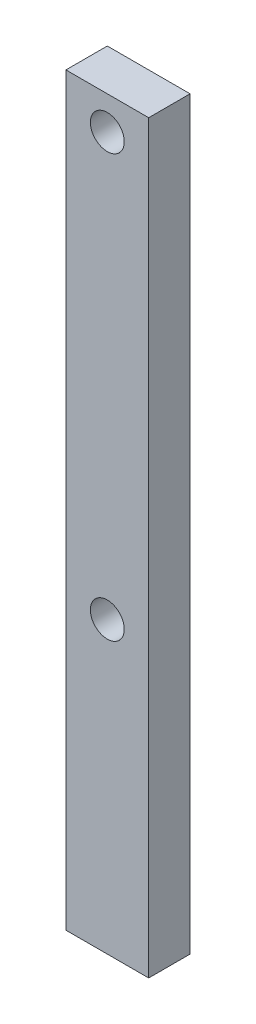
SolidWorks part; units mm, degrees
material "Pin"
ref_plane "Front" through (0, 0, 0) normal (0, 0, 1) x (1, 0, 0)
ref_plane "Top" through (0, 0, 0) normal (0, 1, 0) x (1, 0, 0)
ref_plane "Right" through (0, 0, 0) normal (1, 0, 0) x (0, 0, -1)
sketch "Esquisse1" plane through (0, 0, 0) normal (0, 0, 1) x (1, 0, 0)
  line L1 (-6.35, 57.15) -> (6.35, 57.15)
  line L2 (-6.35, 57.15) -> (-6.35, -57.15)
  line L3 (-6.35, -57.15) -> (6.35, -57.15)
  line L4 (6.35, 57.15) -> (6.35, -57.15)
  line L5 (-6.35, 57.15) -> (6.35, -57.15) construction
  line L6 (-6.35, -57.15) -> (6.35, 57.15) construction
  point P0 (0, 0)
  dimension "D1" = 12.7
  dimension "D2" = 114.3
extrude "Boss.-Extru.1" add sketch "Esquisse1" along normal blind 6.35
sketch "Esquisse3" plane through (0, 0, 6.35) normal (0, 0, 1) x (1, 0, 0)
  line L0 (6.35, 57.15) -> (-6.35, 57.15) construction
  line L1 (-6.35, -57.15) -> (6.35, -57.15) construction
  circle A0 centre (0, -12.7) radius 2.6
  circle A1 centre (0, 52.07) radius 2.6
  point P8 (0, 0)
  dimension "D1" = 5.2
  dimension "D2" = 5.2
  dimension "D3" = 5.08
  dimension "D4" = 44.45
extrude "Enlèv. mat.-Extru.2" cut sketch "Esquisse3" against normal through all
